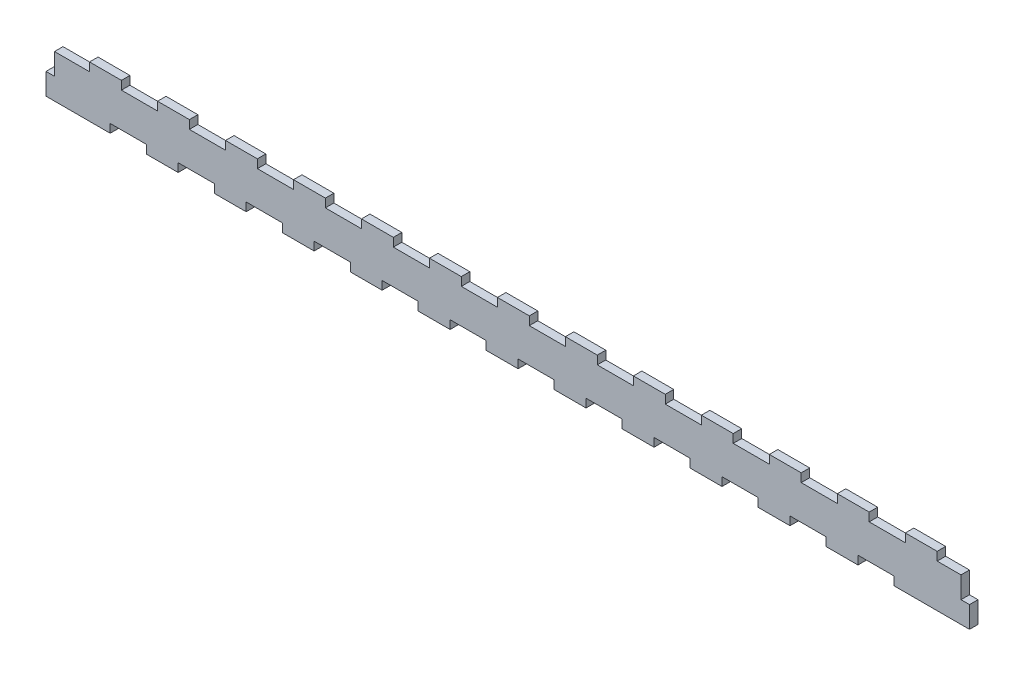
SolidWorks part; units mm, degrees
ref_plane "Plan de face" through (0, 0, 0) normal (0, 0, 1) x (1, 0, 0)
ref_plane "Plan de dessus" through (0, 0, 0) normal (0, 1, 0) x (1, 0, 0)
ref_plane "Plan de droite" through (0, 0, 0) normal (1, 0, 0) x (0, 0, -1)
sketch "Esquisse1" plane through (0, 0, 0) normal (0, 0, 1) x (1, 0, 0)
  line L6 (108.68, -6.055) -> (-108.68, -6.055)
  line L8 (108.68, -6.055) -> (108.68, 6.055)
  line L9 (108.68, 6.055) -> (-108.68, 6.055)
  line L10 (-108.68, -6.055) -> (-108.68, 6.055)
  point P4 (0, 0)
extrude "Boss.-Extru.1" add sketch "Esquisse1" along normal blind 2
sketch "Esquisse2" plane through (0, 0, 0) normal (0, 0, -1) x (-1, 0, 0)
  line L0 (-108.68, 6.055) -> (-101.32, 6.055) construction
  line L1 (-109.57, 4.055) -> (-101.07, 4.055)
  line L2 (-109.57, 4.055) -> (-109.57, 6.305)
  line L3 (-109.57, 6.305) -> (-101.07, 6.305)
  line L4 (-101.07, 4.055) -> (-101.07, 6.305)
  line L9 (-93.32, 4.055) -> (-93.32, 6.055) construction
  line L10 (-101.32, 6.055) -> (-101.32, 4.055) construction
  line L12 (-85.07, 4.055) -> (-85.07, 6.305)
  line L13 (-93.57, 6.305) -> (-85.07, 6.305)
  line L14 (-93.57, 4.055) -> (-93.57, 6.305)
  line L15 (-93.57, 4.055) -> (-85.07, 4.055)
  line L16 (-69.07, 4.055) -> (-69.07, 6.305)
  line L17 (-77.57, 6.305) -> (-69.07, 6.305)
  line L18 (-77.57, 4.055) -> (-77.57, 6.305)
  line L19 (-77.57, 4.055) -> (-69.07, 4.055)
  line L20 (-53.07, 4.055) -> (-53.07, 6.305)
  line L21 (-61.57, 6.305) -> (-53.07, 6.305)
  line L22 (-61.57, 4.055) -> (-61.57, 6.305)
  line L23 (-61.57, 4.055) -> (-53.07, 4.055)
  line L24 (-37.07, 4.055) -> (-37.07, 6.305)
  line L25 (-45.57, 6.305) -> (-37.07, 6.305)
  line L26 (-45.57, 4.055) -> (-45.57, 6.305)
  line L27 (-45.57, 4.055) -> (-37.07, 4.055)
  line L28 (-21.07, 4.055) -> (-21.07, 6.305)
  line L29 (-29.57, 6.305) -> (-21.07, 6.305)
  line L30 (-29.57, 4.055) -> (-29.57, 6.305)
  line L31 (-29.57, 4.055) -> (-21.07, 4.055)
  line L32 (-5.07, 4.055) -> (-5.07, 6.305)
  line L33 (-13.57, 6.305) -> (-5.07, 6.305)
  line L34 (-13.57, 4.055) -> (-13.57, 6.305)
  line L35 (-13.57, 4.055) -> (-5.07, 4.055)
  line L36 (10.93, 4.055) -> (10.93, 6.305)
  line L37 (2.43, 6.305) -> (10.93, 6.305)
  line L38 (2.43, 4.055) -> (2.43, 6.305)
  line L39 (2.43, 4.055) -> (10.93, 4.055)
  line L40 (26.93, 4.055) -> (26.93, 6.305)
  line L41 (18.43, 6.305) -> (26.93, 6.305)
  line L42 (18.43, 4.055) -> (18.43, 6.305)
  line L43 (18.43, 4.055) -> (26.93, 4.055)
  line L44 (42.93, 4.055) -> (42.93, 6.305)
  line L45 (34.43, 6.305) -> (42.93, 6.305)
  line L46 (34.43, 4.055) -> (34.43, 6.305)
  line L47 (34.43, 4.055) -> (42.93, 4.055)
  line L48 (58.93, 4.055) -> (58.93, 6.305)
  line L49 (50.43, 6.305) -> (58.93, 6.305)
  line L50 (50.43, 4.055) -> (50.43, 6.305)
  line L51 (50.43, 4.055) -> (58.93, 4.055)
  line L52 (74.93, 4.055) -> (74.93, 6.305)
  line L53 (66.43, 6.305) -> (74.93, 6.305)
  line L54 (66.43, 4.055) -> (66.43, 6.305)
  line L55 (66.43, 4.055) -> (74.93, 4.055)
  line L56 (90.93, 4.055) -> (90.93, 6.305)
  line L57 (82.43, 6.305) -> (90.93, 6.305)
  line L58 (82.43, 4.055) -> (82.43, 6.305)
  line L59 (82.43, 4.055) -> (90.93, 4.055)
  line L60 (90.68, 6.055) -> (90.68, 4.055) construction
  line L61 (98.68, 4.055) -> (98.68, 6.055) construction
  line L62 (98.43, 4.055) -> (108.93, 4.055)
  line L63 (98.43, 4.055) -> (98.43, 6.305)
  line L64 (98.43, 6.305) -> (108.93, 6.305)
  line L65 (108.93, 4.055) -> (108.93, 6.305)
  line L66 (108.68, 6.055) -> (108.68, -6.055) construction
  line L68 (108.68, 6.055) -> (98.68, 6.055) construction
  line L70 (-90.93, -4.055) -> (-82.43, -4.055)
  line L71 (-90.93, -4.055) -> (-90.93, -6.305)
  line L72 (-90.93, -6.305) -> (-82.43, -6.305)
  line L73 (-82.43, -4.055) -> (-82.43, -6.305)
  line L74 (-90.68, -6.055) -> (-90.68, -4.055) construction
  line L75 (-90.68, -6.055) -> (-82.68, -6.055) construction
  line L76 (-82.68, -6.055) -> (-82.68, -4.055) construction
  line L77 (-74.93, -4.055) -> (-74.93, -6.305)
  line L78 (-74.93, -4.055) -> (-66.43, -4.055)
  line L79 (-66.43, -4.055) -> (-66.43, -6.305)
  line L80 (-74.93, -6.305) -> (-66.43, -6.305)
  line L81 (-58.93, -4.055) -> (-58.93, -6.305)
  line L82 (-58.93, -4.055) -> (-50.43, -4.055)
  line L83 (-50.43, -4.055) -> (-50.43, -6.305)
  line L84 (-58.93, -6.305) -> (-50.43, -6.305)
  line L85 (-42.93, -4.055) -> (-42.93, -6.305)
  line L86 (-42.93, -4.055) -> (-34.43, -4.055)
  line L87 (-34.43, -4.055) -> (-34.43, -6.305)
  line L88 (-42.93, -6.305) -> (-34.43, -6.305)
  line L89 (-26.93, -4.055) -> (-26.93, -6.305)
  line L90 (-26.93, -4.055) -> (-18.43, -4.055)
  line L91 (-18.43, -4.055) -> (-18.43, -6.305)
  line L92 (-26.93, -6.305) -> (-18.43, -6.305)
  line L93 (-10.93, -4.055) -> (-10.93, -6.305)
  line L94 (-10.93, -4.055) -> (-2.43, -4.055)
  line L95 (-2.43, -4.055) -> (-2.43, -6.305)
  line L96 (-10.93, -6.305) -> (-2.43, -6.305)
  line L97 (5.07, -4.055) -> (5.07, -6.305)
  line L98 (5.07, -4.055) -> (13.57, -4.055)
  line L99 (13.57, -4.055) -> (13.57, -6.305)
  line L100 (5.07, -6.305) -> (13.57, -6.305)
  line L101 (21.07, -4.055) -> (21.07, -6.305)
  line L102 (21.07, -4.055) -> (29.57, -4.055)
  line L103 (29.57, -4.055) -> (29.57, -6.305)
  line L104 (21.07, -6.305) -> (29.57, -6.305)
  line L105 (37.07, -4.055) -> (37.07, -6.305)
  line L106 (37.07, -4.055) -> (45.57, -4.055)
  line L107 (45.57, -4.055) -> (45.57, -6.305)
  line L108 (37.07, -6.305) -> (45.57, -6.305)
  line L109 (53.07, -4.055) -> (53.07, -6.305)
  line L110 (53.07, -4.055) -> (61.57, -4.055)
  line L111 (61.57, -4.055) -> (61.57, -6.305)
  line L112 (53.07, -6.305) -> (61.57, -6.305)
  line L113 (69.07, -4.055) -> (69.07, -6.305)
  line L114 (69.07, -4.055) -> (77.57, -4.055)
  line L115 (77.57, -4.055) -> (77.57, -6.305)
  line L116 (69.07, -6.305) -> (77.57, -6.305)
  line L117 (85.07, -4.055) -> (85.07, -6.305)
  line L118 (85.07, -4.055) -> (93.57, -4.055)
  line L119 (93.57, -4.055) -> (93.57, -6.305)
  line L120 (85.07, -6.305) -> (93.57, -6.305)
  line L121 (93.32, -6.055) -> (93.32, -4.055) construction
  line L122 (-101.32, 4.055) -> (-108.68, 4.055) construction
  line L123 (-90.68, -4.055) -> (-82.68, -4.055) construction
  dimension "D1" = 0.25
  dimension "D2" = 0.25
  dimension "D3" = 0.25
  dimension "D6" = 0.25
  dimension "D7" = 0.25
  dimension "D8" = 0.25
  dimension "D10" = 0.25
  dimension "D12" = 0.25
  dimension "D13" = 0.25
  dimension "D14" = 0.25
  dimension "D16" = 0.25
  dimension "D5" = 13
  dimension "D15" = 12
extrude "Enlèv. mat.-Extru.1" cut sketch "Esquisse2" against normal through all
sketch "Esquisse4" plane through (0, 0, 0) normal (0, 0, -1) x (-1, 0, 0)
  line L0 (106.68, -1) -> (108.68, -1) construction
  line L1 (106.68, 4.055) -> (108.68, 4.055)
  line L2 (106.68, 4.055) -> (106.68, -1)
  line L3 (106.68, -1) -> (108.68, -1)
  line L4 (108.68, 4.055) -> (108.68, -1)
  line L5 (106.68, 4.055) -> (106.68, -1) construction
extrude "Enlèv. mat.-Extru.2" cut sketch "Esquisse4" against normal through all
mirror "Symétrie1" about plane through (0, 0, 0) normal (1, 0, 0) of "Enlèv. mat.-Extru.2"
